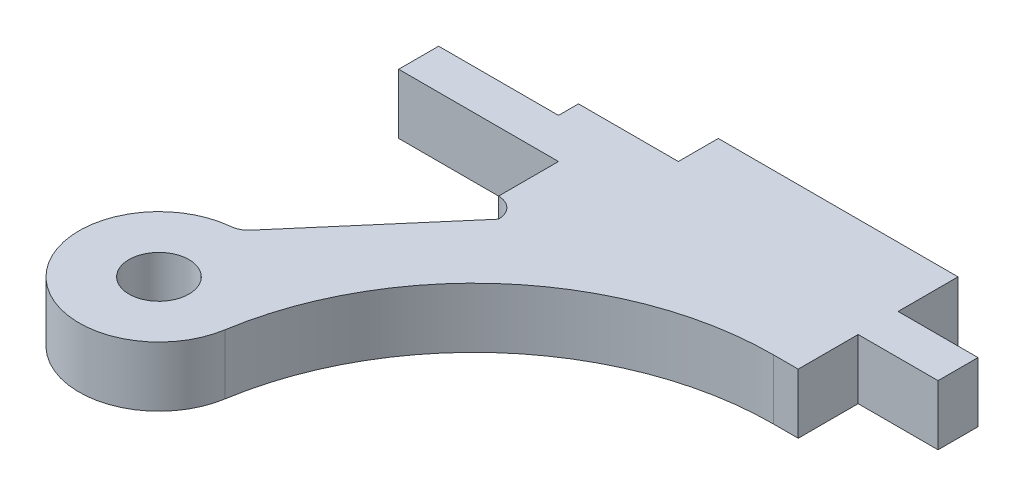
SolidWorks part; units mm, degrees
ref_plane "Alzado" through (0, 0, 0) normal (0, 0, 1) x (1, 0, 0)
ref_plane "Planta" through (0, 0, 0) normal (0, 1, 0) x (1, 0, 0)
ref_plane "Vista lateral" through (0, 0, 0) normal (1, 0, 0) x (0, 0, -1)
sketch "Croquis1" plane through (0, 0, 0) normal (0, 0, 1) x (1, 0, 0)
  line L0 (41421.3053, -442.4395) -> (41421.3053, -439.4395)
  line L1 (41421.3053, -439.4395) -> (41413.3053, -439.4395)
  line L2 (41413.3053, -439.4395) -> (41413.3053, -437.4395)
  line L3 (41413.3053, -437.4395) -> (41419.3053, -437.4395)
  line L4 (41419.3053, -437.4395) -> (41419.3053, -436.4395)
  line L5 (41419.3053, -436.4395) -> (41424.3053, -436.4395)
  line L6 (41424.3053, -436.4395) -> (41424.3053, -434.4395)
  line L7 (41424.3053, -434.4395) -> (41436.3053, -434.4395)
  line L8 (41436.3053, -434.4395) -> (41436.3053, -437.4395)
  line L9 (41436.3053, -437.4395) -> (41440.3053, -437.4395)
  line L10 (41440.3053, -437.4395) -> (41440.3053, -439.4395)
  line L11 (41440.3053, -439.4395) -> (41436.3053, -439.4395)
  line L12 (41436.3053, -439.4395) -> (41436.3053, -442.4395)
  line L13 (41436.3053, -442.4395) -> (41435.0669, -442.4395)
  line L14 (41422.3053, -443.4395) -> (41416.5848, -450.1134)
  arc A0 (41435.0669, -442.4395) -> (41420.2551, -455.0711) centre (41435.0669, -457.4395) ccw
  circle A1 centre (41416.3053, -454.4395) radius 1.5
  arc A2 (41415.9215, -450.4579) -> (41420.2551, -455.0711) centre (41416.3053, -454.4395) ccw
  arc A3 (41422.3053, -443.4395) -> (41421.3053, -442.4395) centre (41421.3053, -443.4395) ccw
  arc A4 (41415.9215, -450.4579) -> (41416.5848, -450.1134) centre (41415.8256, -449.4626) ccw
extrude "Saliente-Extruir1" add sketch "Croquis1" along normal blind 3
move or copy body "Sólido-Mover/Copiar1" bodies to move or copy 101 copy no rotation origin (0, -446.4395, 1.5) rotation axis (-1, 0, 0) rotation angle 90
